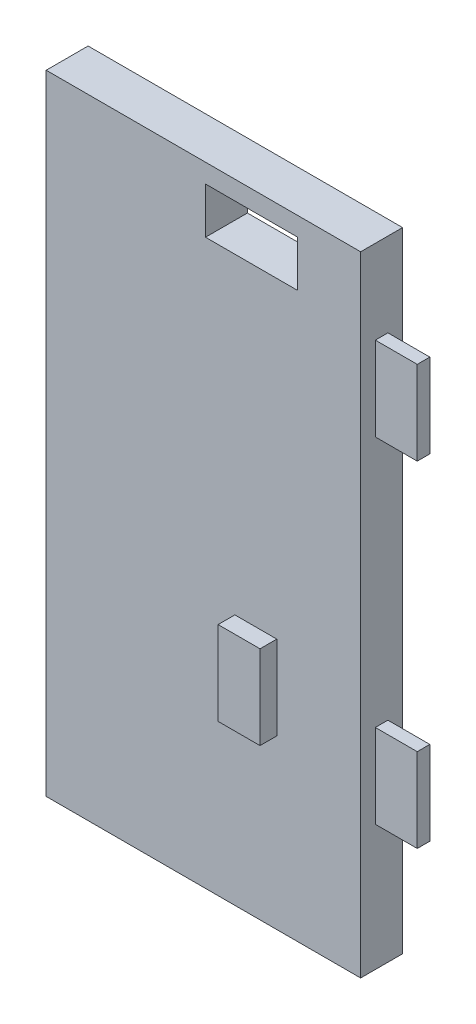
SolidWorks part; units mm, degrees
ref_plane "Front Plane" through (0, 0, 0) normal (1, 0, 0) x (0, 1, 0)
ref_plane "Top Plane" through (0, 0, 0) normal (0, 0, 1) x (0, 1, 0)
ref_plane "Right Plane" through (0, 0, 0) normal (0, 1, 0) x (-1, 0, 0)
sketch "Sketch1" plane through (0, 0, 0) normal (0, 0, 1) x (0, 1, 0)
  line L1 (-75, -37.5) -> (75, -37.5)
  line L2 (-75, -37.5) -> (-75, 37.5)
  line L3 (-75, 37.5) -> (75, 37.5)
  line L4 (75, -37.5) -> (75, 37.5)
  line L5 (-75, -37.5) -> (75, 37.5) construction
  line L6 (-75, 37.5) -> (75, -37.5) construction
  line L7 (59.5, -22.5) -> (70.5, -22.5)
  line L8 (59.5, -22.5) -> (59.5, -0.5)
  line L9 (59.5, -0.5) -> (70.5, -0.5)
  line L10 (70.5, -22.5) -> (70.5, -0.5)
  line L11 (59.5, -22.5) -> (70.5, -0.5) construction
  line L12 (59.5, -0.5) -> (70.5, -22.5) construction
  point P0 (0, 0)
  point P6 (65, -11.5)
  dimension "D1" = 150
  dimension "D2" = 75
  dimension "D3" = 26
  dimension "D4" = 10
  dimension "D5" = 11
  dimension "D6" = 22
extrude "Boss-Extrude1" add sketch "Sketch1" along normal blind 10
sketch "Sketch2" plane through (0, 0, 10) normal (0, 0, 1) x (1, 0, 0)
  line L0 (37.5, -75) -> (37.5, 75) construction
  line L1 (7.5, -35) -> (17.5, -35)
  line L2 (7.5, -35) -> (7.5, -15)
  line L3 (7.5, -15) -> (17.5, -15)
  line L4 (17.5, -35) -> (17.5, -15)
  line L5 (7.5, -35) -> (17.5, -15) construction
  line L6 (7.5, -15) -> (17.5, -35) construction
  line L8 (-37.5, -75) -> (37.5, -75) construction
  point P0 (12.5, -25)
  dimension "D1" = 25
  dimension "D2" = 60
  dimension "D3" = 10
  dimension "D4" = 20
extrude "Boss-Extrude2" add sketch "Sketch2" along normal blind 4
sketch "Sketch3" plane through (37.5, 0, 0) normal (1, 0, 0) x (0, 1, 0)
  line L0 (-75, 0) -> (75, 0) construction
  line L1 (35, 3.5) -> (55, 3.5)
  line L2 (35, 3.5) -> (35, 6.5)
  line L3 (35, 6.5) -> (55, 6.5)
  line L4 (55, 3.5) -> (55, 6.5)
  line L5 (35, 3.5) -> (55, 6.5) construction
  line L6 (35, 6.5) -> (55, 3.5) construction
  line L9 (-45, 3.5) -> (-25, 3.5)
  line L10 (-45, 3.5) -> (-45, 6.5)
  line L11 (-45, 6.5) -> (-25, 6.5)
  line L12 (-25, 3.5) -> (-25, 6.5)
  line L13 (-45, 3.5) -> (-25, 6.5) construction
  line L14 (-45, 6.5) -> (-25, 3.5) construction
  line L15 (-75, 10) -> (-75, 0) construction
  point P0 (45, 5)
  point P9 (-35, 5)
  dimension "D1" = 3
  dimension "D2" = 20
  dimension "D3" = 5
  dimension "D4" = 80
  dimension "D5" = 5
  dimension "D6" = 3
  dimension "D7" = 20
  dimension "D8" = 30
extrude "Boss-Extrude3" add sketch "Sketch3" along normal blind 10
sketch "Sketch4" plane through (0, -75, 0) normal (0, -1, 0) x (1, 0, 0)
  line L0 (-37.5, 0) -> (37.5, 0) construction
  line L1 (-10.25, 3.4) -> (10.25, 3.4)
  line L2 (-10.25, 3.4) -> (-10.25, 6.6)
  line L3 (-10.25, 6.6) -> (10.25, 6.6)
  line L4 (10.25, 3.4) -> (10.25, 6.6)
  line L5 (-10.25, 3.4) -> (10.25, 6.6) construction
  line L6 (-10.25, 6.6) -> (10.25, 3.4) construction
  point P0 (0, 5)
  dimension "D1" = 20.5
  dimension "D2" = 3.2
  dimension "D3" = 5
extrude "Cut-Extrude1" cut sketch "Sketch4" against normal blind 10
